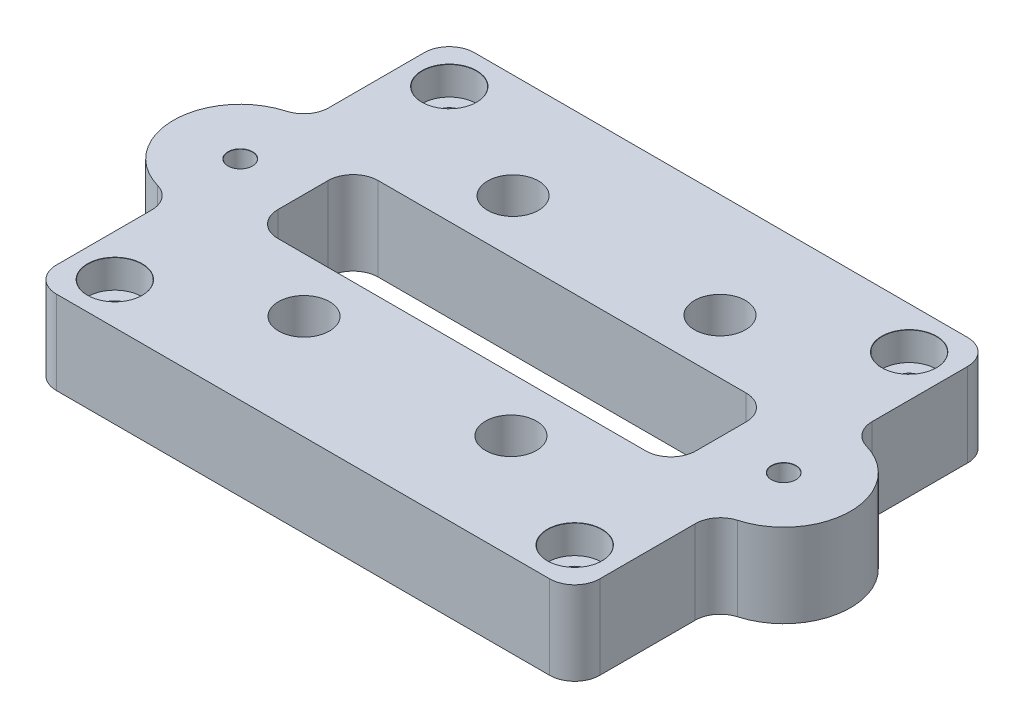
SolidWorks part; units mm, degrees
ref_plane "Front Plane" through (0, 0, 0) normal (0, 0, 1) x (1, 0, 0)
ref_plane "Top Plane" through (0, 0, 0) normal (0, 1, 0) x (1, 0, 0)
ref_plane "Right Plane" through (0, 0, 0) normal (1, 0, 0) x (0, 0, -1)
sketch "Sketch1" plane through (0, 0, 0) normal (0, 1, 0) x (1, 0, 0)
  line L0 (0, 12.5) -> (0, 0) construction
  line L1 (-32.5, 25) -> (32.5, 25)
  line L2 (-32.5, 25) -> (-32.5, -25)
  line L3 (-32.5, -25) -> (32.5, -25)
  line L4 (32.5, 25) -> (32.5, -25)
  line L5 (-32.5, 25) -> (32.5, -25) construction
  line L6 (-32.5, -25) -> (32.5, 25) construction
  line L7 (-12.375, 12.5) -> (12.375, 12.5) construction
  line L8 (-12.375, 12.5) -> (-12.375, -12.5) construction
  line L9 (-12.375, -12.5) -> (12.375, -12.5) construction
  line L10 (12.375, 12.5) -> (12.375, -12.5) construction
  line L11 (0, 0) -> (12.375, 0) construction
  circle A0 centre (-12.375, 12.5) radius 3.05
  circle A1 centre (-12.375, -12.5) radius 3.05
  circle A2 centre (12.375, 12.5) radius 3.05
  circle A3 centre (12.375, -12.5) radius 3.05
  point P0 (0, 0)
  dimension "D3" = 6.1
  dimension "D1" = 65
  dimension "D2" = 50
  dimension "D4" = 25
  dimension "D5" = 24.75
extrude "Boss-Extrude1" add sketch "Sketch1" along normal blind 10
fillet "Fillet1" radius 3 4 edges at (-32.5, 5, -25) (32.5, 5, -25) (-32.5, 5, 25) (32.5, 5, 25)
hole_wizard "CBORE for M3 Hex Socket Head Cap Screw1" positions "Sketch2" profile "Sketch3" counterbore size "M3" standard "ISO" end condition through all
sketch "Sketch2" plane through (0, 10, 0) normal (0, 1, 0) x (1, 0, 0)
  line L12 (27.5, 20) -> (-27.5, 20)
  line L13 (-27.5, 20) -> (-27.5, -20)
  line L14 (-27.5, -20) -> (27.5, -20)
  line L15 (27.5, -20) -> (27.5, 20)
  line L16 (27.5, 20) -> (-27.5, 20)
  line L17 (-27.5, 20) -> (-27.5, -20)
  line L18 (-27.5, -20) -> (27.5, -20)
  line L19 (27.5, -20) -> (27.5, 20)
  point P61 (27.5, 20)
  point P62 (-27.5, 20)
  point P63 (-27.5, -20)
  point P64 (27.5, -20)
  dimension "D1" = 5
sketch "Sketch3" plane through (27.5, 10, -20) normal (1, 0, 0) x (0, 0, 1)
  line L0 (0, 0) -> (0, 10)
  line L1 (0, 10) -> (1.7, 10)
  line L3 (1.7, 10) -> (1.7, 3.4)
  line L4 (3.25, 3.4) -> (1.7, 3.4)
  line L5 (3.25, 3.4) -> (3.25, 0.025)
  line L6 (3.25, 0.025) -> (3.275, 0)
  line L7 (3.275, 0) -> (0, 0)
  line L8 (-3.25, 0.025) -> (-3.275, 0) construction
  line L11 (0, -6.35) -> (0, 107.95) construction
  dimension "Thru Hole Dia." = 3.4
  dimension "Thru Hole Depth" = 10
  dimension "C'Bore Dia." = 6.5
  dimension "C'Bore Depth" = 3.4
  dimension "Near C'Sink Dia." = 6.55
  dimension "Near C'Sink Angle" = 90
sketch "Sketch6" plane through (0, 10, 0) normal (0, 1, 0) x (1, 0, 0)
  line L0 (-32.5, 22) -> (-32.5, -22) construction
  line L1 (32.5, -22) -> (32.5, 22) construction
  circle A0 centre (-32.5, 0) radius 8
  circle A1 centre (32.5, 0) radius 8
  dimension "D1" = 16
extrude "Boss-Extrude2" add sketch "Sketch6" against normal up to surface (10 mm away) up to face at (27.5, 0, -18.3)
fillet "Fillet2" radius 3 4 edges at (32.5, 5, 8) (32.5, 5, -8) (-32.5, 5, -8) (-32.5, 5, 8)
hole_wizard "Ø2.9 (2.9) Diameter Hole1" positions "Sketch7" profile "Sketch8" hole size "Ø2.9" standard "ISO"
sketch "Sketch7" plane through (0, 10, 0) normal (0, 1, 0) x (1, 0, 0)
  point P0 (-32.5, 0)
  point P3 (32.5, 0)
sketch "Sketch8" plane through (-32.5, 10, 0) normal (1, 0, 0) x (0, 0, 1)
  line L0 (0, 0) -> (0, 6.8712)
  line L1 (0, 6.8712) -> (1.45, 6)
  line L2 (1.45, 6) -> (1.45, 0.025)
  line L3 (1.45, 0.025) -> (1.475, 0)
  line L5 (1.475, 0) -> (0, 0)
  line L6 (-1.45, 0.025) -> (-1.475, 0) construction
  line L10 (0, 6.8712) -> (-1.45, 6) construction
  line L11 (0, -6.35) -> (0, 107.95) construction
  dimension "Hole Dia." = 2.9
  dimension "Hole Depth" = 6
  dimension "Near C'Sink Dia." = 2.95
  dimension "Near C'Sink Angle" = 90
  dimension "Drill Angle" = 118
sketch "Sketch9" plane through (0, 10, 0) normal (0, 1, 0) x (1, 0, 0)
  line L1 (-22, 6) -> (22, 6)
  line L2 (-25, 3) -> (-25, -3)
  line L3 (-22, -6) -> (22, -6)
  line L4 (25, 3) -> (25, -3)
  line L5 (-25, 6) -> (25, -6) construction
  line L6 (-25, -6) -> (25, 6) construction
  arc A0 (22, -6) -> (25, -3) centre (22, -3) ccw
  arc A1 (22, 6) -> (25, 3) centre (22, 3) cw
  arc A2 (-25, -3) -> (-22, -6) centre (-22, -3) ccw
  arc A3 (-22, 6) -> (-25, 3) centre (-22, 3) ccw
  point P0 (0, 0)
  dimension "D3" = 3
  dimension "D1" = 12
  dimension "D2" = 50
extrude "Cut-Extrude1" cut sketch "Sketch9" against normal blind 10
